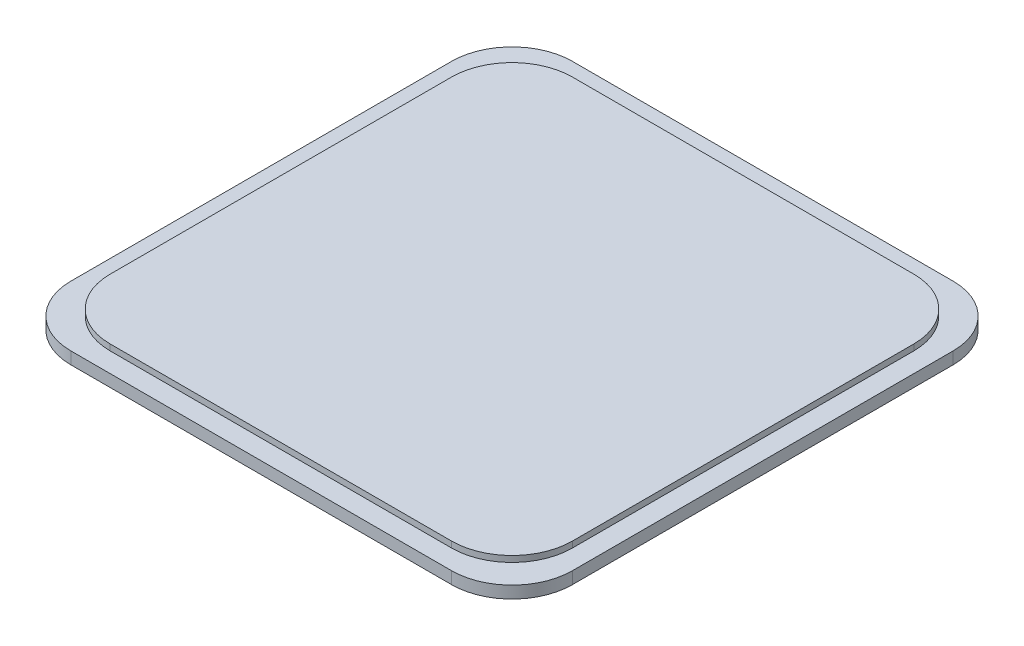
SolidWorks part; units mm, degrees
ref_plane "前视基准面" through (0, 0, 0) normal (0, 0, 1) x (1, 0, 0)
ref_plane "上视基准面" through (0, 0, 0) normal (0, 1, 0) x (1, 0, 0)
ref_plane "右视基准面" through (0, 0, 0) normal (1, 0, 0) x (0, 0, -1)
other "Configuration Table"
sketch "Sketch1" plane through (0, 0, 0) normal (0, 1, 0) x (1, 0, 0)
  line L1 (-31.5, 41.5) -> (31.5, 41.5)
  line L2 (-41.5, 31.5) -> (-41.5, -31.5)
  line L3 (-31.5, -41.5) -> (31.5, -41.5)
  line L4 (41.5, 31.5) -> (41.5, -31.5)
  line L5 (-41.5, 41.5) -> (41.5, -41.5) construction
  line L6 (-41.5, -41.5) -> (41.5, 41.5) construction
  arc A0 (31.5, -41.5) -> (41.5, -31.5) centre (31.5, -31.5) ccw
  arc A1 (-41.5, -31.5) -> (-31.5, -41.5) centre (-31.5, -31.5) ccw
  arc A2 (31.5, 41.5) -> (41.5, 31.5) centre (31.5, 31.5) cw
  arc A3 (-31.5, 41.5) -> (-41.5, 31.5) centre (-31.5, 31.5) ccw
  point P0 (0, 0)
  dimension "D3" = 10
  dimension "D1" = 83
  dimension "D2" = 83
extrude "Boss-Extrude1" add sketch "Sketch1" along normal blind 2
sketch "Sketch2" plane through (0, 2, 0) normal (0, 1, 0) x (1, 0, 0)
  line L1 (-28.25, 38.25) -> (28.25, 38.25)
  line L2 (-38.25, 28.25) -> (-38.25, -28.25)
  line L3 (-28.25, -38.25) -> (28.25, -38.25)
  line L4 (38.25, 28.25) -> (38.25, -28.25)
  line L5 (-38.25, 38.25) -> (38.25, -38.25) construction
  line L6 (-38.25, -38.25) -> (38.25, 38.25) construction
  arc A0 (-38.25, -28.25) -> (-28.25, -38.25) centre (-28.25, -28.25) ccw
  arc A1 (28.25, -38.25) -> (38.25, -28.25) centre (28.25, -28.25) ccw
  arc A2 (28.25, 38.25) -> (38.25, 28.25) centre (28.25, 28.25) cw
  arc A3 (-28.25, 38.25) -> (-38.25, 28.25) centre (-28.25, 28.25) ccw
  point P0 (0, 0)
  dimension "D3" = 10
  dimension "D1" = 76.5
  dimension "D2" = 76.5
extrude "Boss-Extrude2" add sketch "Sketch2" along normal blind 1
